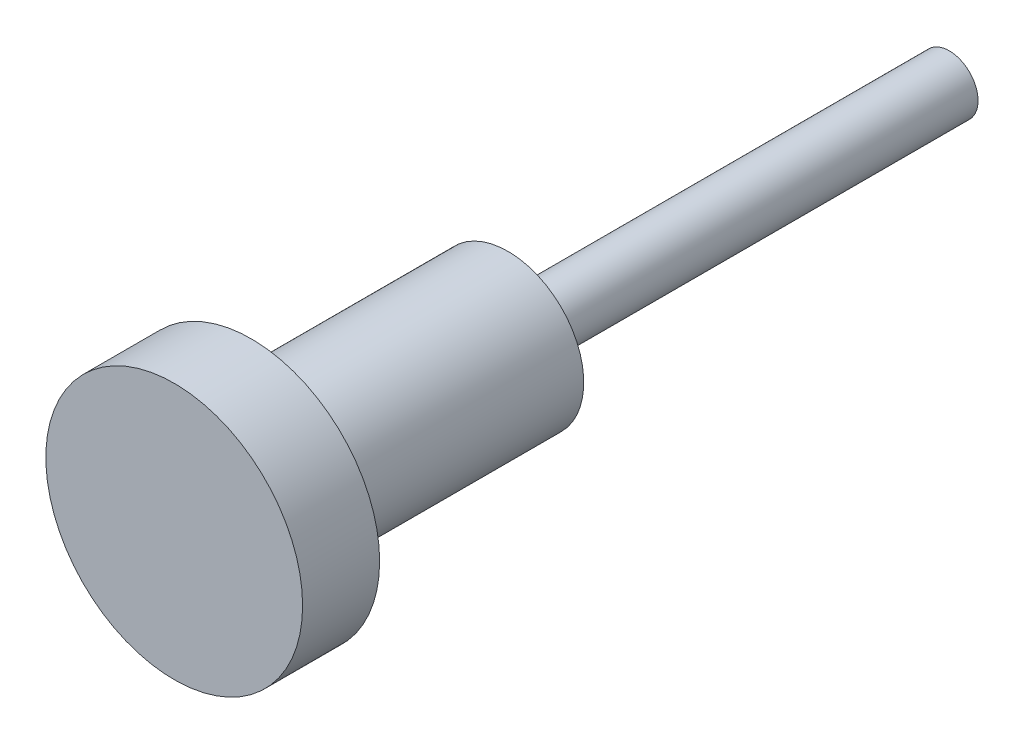
SolidWorks part; units mm, degrees
ref_plane "前视基准面" through (0, 0, 0) normal (0, 0, 1) x (1, 0, 0)
ref_plane "上视基准面" through (0, 0, 0) normal (0, 1, 0) x (1, 0, 0)
ref_plane "右视基准面" through (0, 0, 0) normal (1, 0, 0) x (0, 0, -1)
other "Configuration Table"
sketch "草图1" plane through (0, 0, 0) normal (0, 0, 1) x (1, 0, 0)
  circle A0 centre (0, 0) radius 5
extrude "凸台-拉伸1" add sketch "草图1" along normal blind 3
sketch "草图2" plane through (0, 0, 0) normal (0, 0, -1) x (-1, 0, 0)
  circle A0 centre (0, 0) radius 2.9488
extrude "凸台-拉伸2" add sketch "草图2" along normal blind 10
sketch "草图3" plane through (0, 0, -10) normal (0, 0, -1) x (-1, 0, 0)
  circle A0 centre (0, 0) radius 1.1223
extrude "凸台-拉伸3" add sketch "草图3" along normal blind 17.1825
